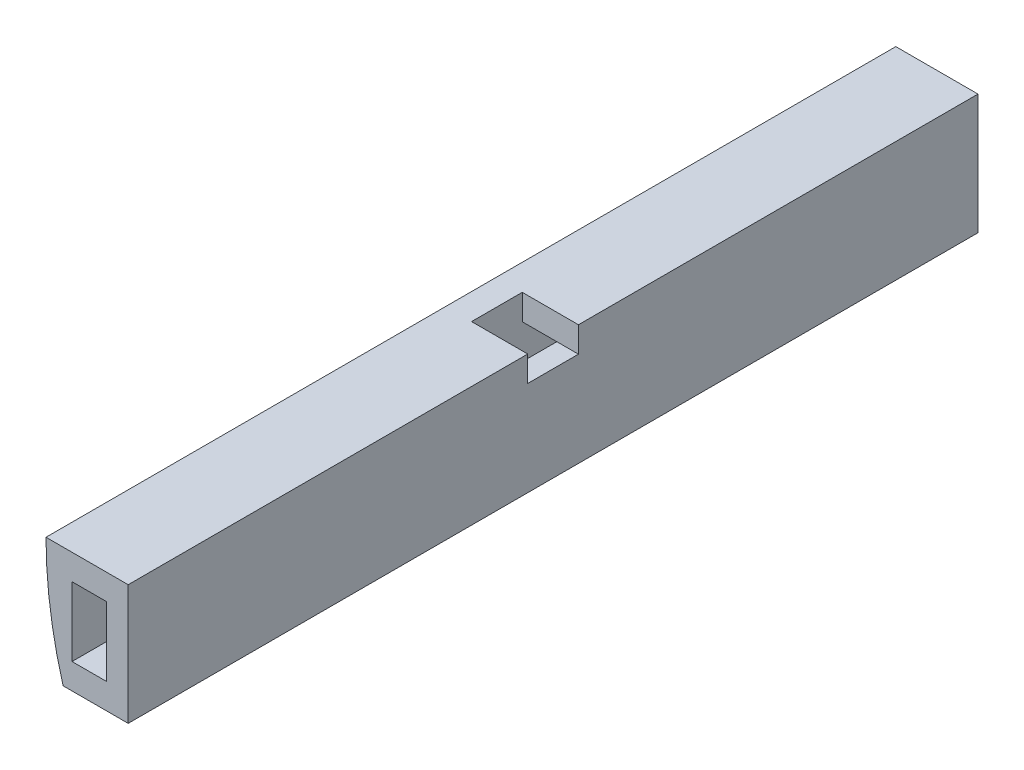
SolidWorks part; units mm, degrees
ref_plane "Front Plane" through (0, 0, 0) normal (0, 0, 1) x (1, 0, 0)
ref_plane "Top Plane" through (0, 0, 0) normal (0, 1, 0) x (1, 0, 0)
ref_plane "Right Plane" through (0, 0, 0) normal (1, 0, 0) x (0, 0, -1)
sketch "Sketch1" plane through (0, 0, 0) normal (0, 0, 1) x (1, 0, 0)
  line L0 (-65.388, -4.4958) -> (-65.388, -16.6878)
  line L1 (-76.073, 0) -> (-65.388, 0)
  line L2 (-76.073, 4.4958) -> (-76.073, -4.4958)
  line L3 (-76.073, -4.4958) -> (-65.388, -4.4958)
  line L4 (-65.388, 4.4958) -> (-65.388, -4.4958)
  line L5 (-65.388, -16.6878) -> (-71.484, -16.6878)
  line L6 (-71.484, -16.6878) -> (-71.484, -4.4958)
  line L7 (-71.484, -16.6878) -> (-74.2201, -16.6878)
  line L8 (-65.388, -16.6878) -> (-65.388, -21.1836)
  line L9 (-65.388, -21.1836) -> (-73.0641, -21.1836)
  line L10 (-65.388, 0) -> (-61.578, 0)
  line L11 (-61.578, 0) -> (-61.578, -21.1836)
  line L12 (-61.578, -21.1836) -> (-65.388, -21.1836)
  line L13 (-65.388, -4.4958) -> (-61.578, -4.4958)
  line L14 (-13.638, 0) -> (-100.3142, 0) construction
  line L15 (-76.073, 4.4958) -> (-65.388, 4.4958)
  line L16 (-71.484, -4.4958) -> (-71.484, 0)
  circle A0 centre (0, 0) radius 76.073
  circle A1 centre (0, 0) radius 73.406
  dimension "D1" = 152.146
  dimension "D2" = 146.812
  dimension "D3" = 4.4958
  dimension "D4" = 12.192
  dimension "D5" = 6.096
  dimension "D6" = 4.4958
  dimension "D7" = 3.81
extrude "Boss-Extrude1" add sketch "Sketch1" along normal blind 149.86 contours A1 L3 A0 L7 | L3 A1 L6 | A1 L7 A0 L9 | L5 A1 L9 L8 | L12 L11 L10 L4 L0 L8 | A1 L1 A0 L3 | L1 A1 L3 L16
sketch "Sketch2" plane through (0, 0, 149.86) normal (0, 0, 1) x (1, 0, 0)
  line L1 (-61.578, -4.4958) -> (-71.484, -4.4958)
  line L2 (-61.578, -4.4958) -> (-61.578, 0)
  line L3 (-61.578, 0) -> (-71.484, 0)
  line L4 (-71.484, -4.4958) -> (-71.484, 0)
extrude "Boss-Extrude2" add sketch "Sketch2" against normal blind 70.4596
sketch "Sketch3" plane through (0, 0, 0) normal (0, 0, -1) x (-1, 0, 0)
  line L1 (61.578, -4.4958) -> (71.484, -4.4958)
  line L2 (61.578, -4.4958) -> (61.578, 0)
  line L3 (61.578, 0) -> (71.484, 0)
  line L4 (71.484, -4.4958) -> (71.484, 0)
extrude "Boss-Extrude3" add sketch "Sketch3" against normal blind 70.4596
